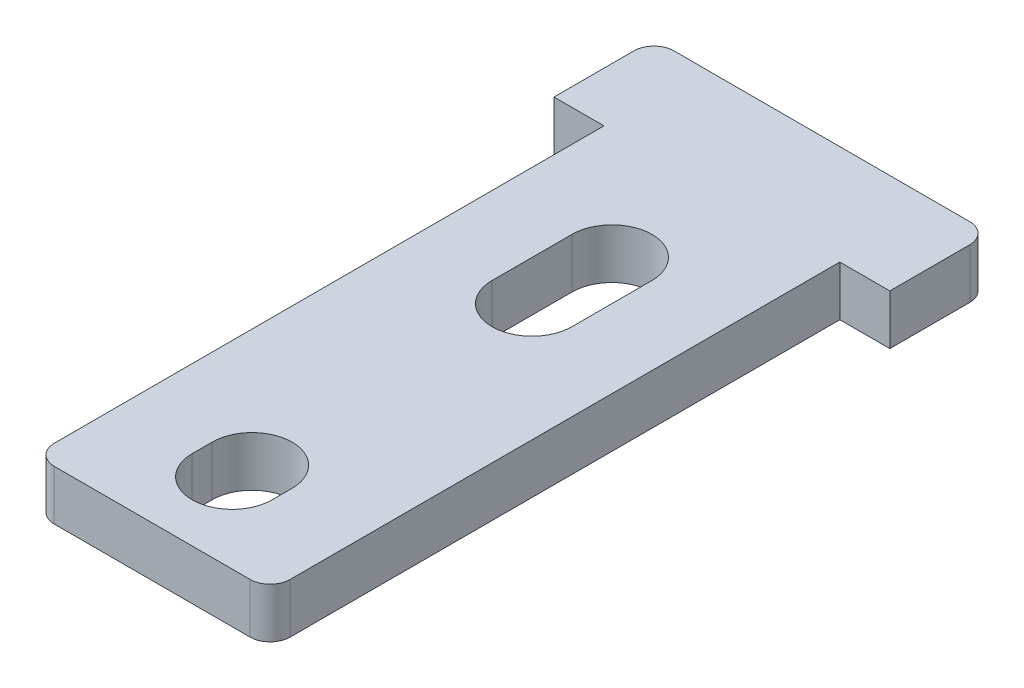
SolidWorks part; units mm, degrees
ref_plane "Alzado" through (0, 0, 0) normal (0, 0, 1) x (1, 0, 0)
ref_plane "Planta" through (0, 0, 0) normal (0, 1, 0) x (1, 0, 0)
ref_plane "Vista lateral" through (0, 0, 0) normal (1, 0, 0) x (0, 0, -1)
sketch "Croquis1" plane through (0, 0, 0) normal (0, 1, 0) x (1, 0, 0)
  line L0 (0, 0) -> (9.8, 0)
  line L1 (10.8, 1) -> (10.8, 28.5)
  line L2 (10.8, 28.5) -> (13.3, 28.5)
  line L3 (13.3, 28.5) -> (13.3, 32.5)
  line L4 (4.9, 0) -> (4.9, 2) construction
  line L5 (-2.5, 33.5) -> (12.3, 33.5)
  line L6 (13.3, 33.5) -> (13.3674, 33.5462)
  line L7 (-3.5, 33.5) -> (-3.5674, 33.5462)
  line L8 (-3.5, 28.5) -> (-3.5, 32.5)
  line L9 (-1, 28.5) -> (-3.5, 28.5)
  line L10 (-1, 1) -> (-1, 28.5)
  line L11 (4.9, 2) -> (4.9, 4) construction
  line L12 (6.9, 4) -> (6.9, 5)
  line L13 (4.9, 4) -> (4.9, 5) construction
  line L14 (2.9, 5) -> (2.9, 4)
  line L15 (4.9, 7) -> (4.9, 17) construction
  line L16 (4.9, 17) -> (4.9, 19) construction
  line L17 (6.9, 19) -> (6.9, 23)
  line L18 (2.9, 19) -> (2.9, 23)
  line L19 (4.9, 19) -> (4.9, 23) construction
  arc A0 (12.3, 33.5) -> (13.3, 32.5) centre (12.3, 32.5) cw
  arc A1 (9.8, 0) -> (10.8, 1) centre (9.8, 1) ccw
  arc A2 (0, 0) -> (-1, 1) centre (0, 1) cw
  arc A3 (-2.5, 33.5) -> (-3.5, 32.5) centre (-2.5, 32.5) ccw
  arc A4 (2.9, 4) -> (6.9, 4) centre (4.9, 4) ccw
  arc A5 (6.9, 5) -> (2.9, 5) centre (4.9, 5) ccw
  arc A6 (2.9, 19) -> (6.9, 19) centre (4.9, 19) ccw
  arc A7 (6.9, 23) -> (2.9, 23) centre (4.9, 23) ccw
  point P14 (10.8, 0)
  point P24 (-1, 0)
  dimension "D5" = 1
  dimension "D6" = 1
  dimension "D1" = 2
  dimension "D2" = 28.5
  dimension "D3" = 2.5
  dimension "D4" = 5
  dimension "D7" = 2
  dimension "D8" = 1
  dimension "D9" = 10
  dimension "D10" = 2
  dimension "D11" = 4
extrude "Saliente-Extruir1" add sketch "Croquis1" along normal blind 2.5 contours L5 A3 L8 L9 L10 A2 L0 A1 L1 L2 L3 A0 A7 L17 A6 L18 A5 L12 A4 L14
